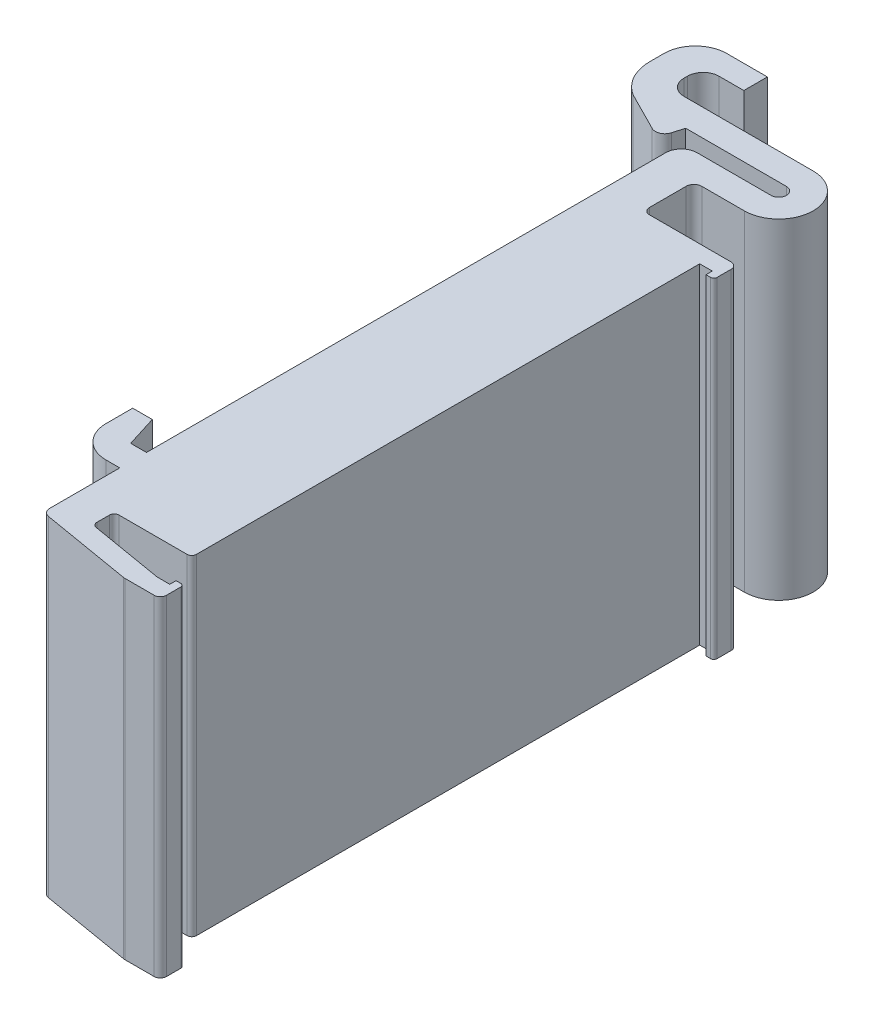
SolidWorks part; units mm, degrees
ref_plane "Front Plane" through (0, 0, 0) normal (0, 0, 1) x (1, 0, 0)
ref_plane "Top Plane" through (0, 0, 0) normal (0, 1, 0) x (1, 0, 0)
ref_plane "Right Plane" through (0, 0, 0) normal (1, 0, 0) x (0, 0, -1)
sketch "Sketch1" plane through (0, 0, 0) normal (0, 1, 0) x (1, 0, 0)
  line L9 (-57.1064, -7.4648) -> (-59.6294, -7.4648)
  line L10 (-60.6294, -6.4648) -> (-60.6294, -6.2388)
  line L11 (-59.6294, -5.2388) -> (-58.0464, -5.2388)
  line L12 (-58.0464, -5.2388) -> (-58.0464, -3.7418)
  line L13 (-58.0464, -3.7418) -> (-60.6294, -3.7418)
  line L14 (-62.6264, -5.7388) -> (-62.6264, -6.6468)
  line L15 (-61.3323, -8.9964) -> (-58.8671, -10.2434)
  line L16 (-58.0222, -9.872) -> (-57.8194, -9.1648)
  line L17 (-57.8194, -9.1648) -> (-51.4064, -9.1648)
  line L18 (-51.4064, -10.1508) -> (-56.1064, -10.1508)
  line L19 (-57.1064, -11.1508) -> (-57.1064, -44.1648)
  line L20 (-57.1064, -44.1648) -> (-58.1114, -44.1648)
  line L21 (-58.1114, -44.1648) -> (-58.7384, -42.1648)
  line L22 (-58.7384, -42.1648) -> (-59.9844, -42.1648)
  line L23 (-59.9844, -42.1648) -> (-59.9844, -43.8648)
  line L24 (-57.9844, -45.8648) -> (-57.1064, -45.8648)
  line L61 (-54.1064, -11.8508) -> (-51.4064, -11.8508)
  line L62 (-51.4064, -7.4648) -> (-54.1064, -7.4648)
  line L72 (-57.1064, -7.4648) -> (-54.1064, -7.4648)
  line L76 (-53.8064, -15.0851) -> (-49.0064, -15.0851)
  line L77 (-48.6064, -15.4851) -> (-48.6064, -16.3851)
  line L78 (-48.8064, -16.5851) -> (-49.1064, -16.5851)
  line L79 (-49.1064, -16.5851) -> (-49.1064, -16.1851)
  line L80 (-49.1064, -16.1851) -> (-49.9064, -16.1851)
  line L81 (-49.9064, -16.1851) -> (-49.9064, -16.5851)
  line L95 (-49.0064, -51.7851) -> (-50.8644, -51.7851)
  line L96 (-54.6064, -14.5851) -> (-54.6064, -12.3508)
  line L100 (-57.1064, -45.8648) -> (-57.1064, -50.3127)
  line L103 (-49.9064, -16.5851) -> (-49.9064, -48.1851)
  line L106 (-49.8223, -50.6851) -> (-49.1064, -50.6851)
  line L107 (-49.1064, -50.6851) -> (-49.1064, -50.2851)
  line L108 (-49.1064, -50.2851) -> (-48.8064, -50.2851)
  line L109 (-48.6064, -50.4851) -> (-48.6064, -51.3851)
  line L110 (-50.9479, -51.7781) -> (-56.6899, -50.8056)
  line L111 (-54.6064, -14.5851) -> (-54.6064, -14.6851)
  line L112 (-54.2064, -15.0851) -> (-53.8064, -15.0851)
  line L113 (-49.9893, -50.6711) -> (-54.5863, -49.8925)
  line L114 (-54.8362, -49.5968) -> (-54.8362, -48.7851)
  line L115 (-54.5362, -48.4851) -> (-50.2064, -48.4851)
  arc A4 (-59.6294, -7.4648) -> (-60.6294, -6.4648) centre (-59.6294, -6.4648) cw
  arc A5 (-60.6294, -6.2388) -> (-59.6294, -5.2388) centre (-59.6294, -6.2388) cw
  arc A6 (-60.6294, -3.7418) -> (-62.6264, -5.7388) centre (-60.6294, -5.7388) ccw
  arc A7 (-62.6264, -6.6468) -> (-61.3323, -8.9964) centre (-59.8464, -6.6468) ccw
  arc A8 (-58.8671, -10.2434) -> (-58.0222, -9.872) centre (-58.5974, -9.7103) ccw
  arc A9 (-51.4064, -9.1648) -> (-51.4064, -10.1508) centre (-51.4064, -9.6578) cw
  arc A10 (-56.1064, -10.1508) -> (-57.1064, -11.1508) centre (-56.1064, -11.1508) ccw
  arc A11 (-59.9844, -43.8648) -> (-57.9844, -45.8648) centre (-57.9844, -43.8648) ccw
  arc A26 (-51.4064, -11.8508) -> (-51.4064, -7.4648) centre (-51.4064, -9.6578) ccw
  arc A34 (-48.6064, -51.3851) -> (-49.0064, -51.7851) centre (-49.0064, -51.3851) cw
  arc A35 (-49.0064, -15.0851) -> (-48.6064, -15.4851) centre (-49.0064, -15.4851) cw
  arc A40 (-54.6064, -12.3508) -> (-54.1064, -11.8508) centre (-54.1064, -12.3508) cw
  arc A44 (-54.6064, -14.6851) -> (-54.2064, -15.0851) centre (-54.2064, -14.6851) ccw
  arc A46 (-57.1064, -50.3127) -> (-56.6899, -50.8056) centre (-56.6064, -50.3127) ccw
  arc A47 (-50.8644, -51.7851) -> (-50.9479, -51.7781) centre (-50.8644, -51.2851) cw
  arc A48 (-48.6064, -16.3851) -> (-48.8064, -16.5851) centre (-48.8064, -16.3851) cw
  arc A49 (-48.8064, -50.2851) -> (-48.6064, -50.4851) centre (-48.8064, -50.4851) cw
  arc A52 (-49.8223, -50.6851) -> (-49.9893, -50.6711) centre (-49.8223, -49.6851) cw
  arc A53 (-49.9064, -48.1851) -> (-50.2064, -48.4851) centre (-50.2064, -48.1851) cw
  arc A54 (-54.8362, -48.7851) -> (-54.5362, -48.4851) centre (-54.5362, -48.7851) cw
  arc A55 (-54.5863, -49.8925) -> (-54.8362, -49.5968) centre (-54.5362, -49.5968) cw
  point P15 (-48.6064, -51.7851)
  point P54 (-49.9064, -50.6851)
  point P63 (-50.9064, -51.7851)
  point P67 (-48.6064, -16.5851)
  point P74 (-48.6064, -50.2851)
  point P82 (-54.8362, -49.8502)
  dimension "D3" = 5
  dimension "D5" = 1
  dimension "D2" = 0.4
  dimension "D11" = 0.2
  dimension "D6" = 0.3
  dimension "D4" = 2.3
  dimension "D7" = 0.5
  dimension "D8" = 0.5
  dimension "D9" = 0.8
  dimension "D10" = 1.5
extrude "Boss-Extrude2" add sketch "Sketch1" along normal blind 21
